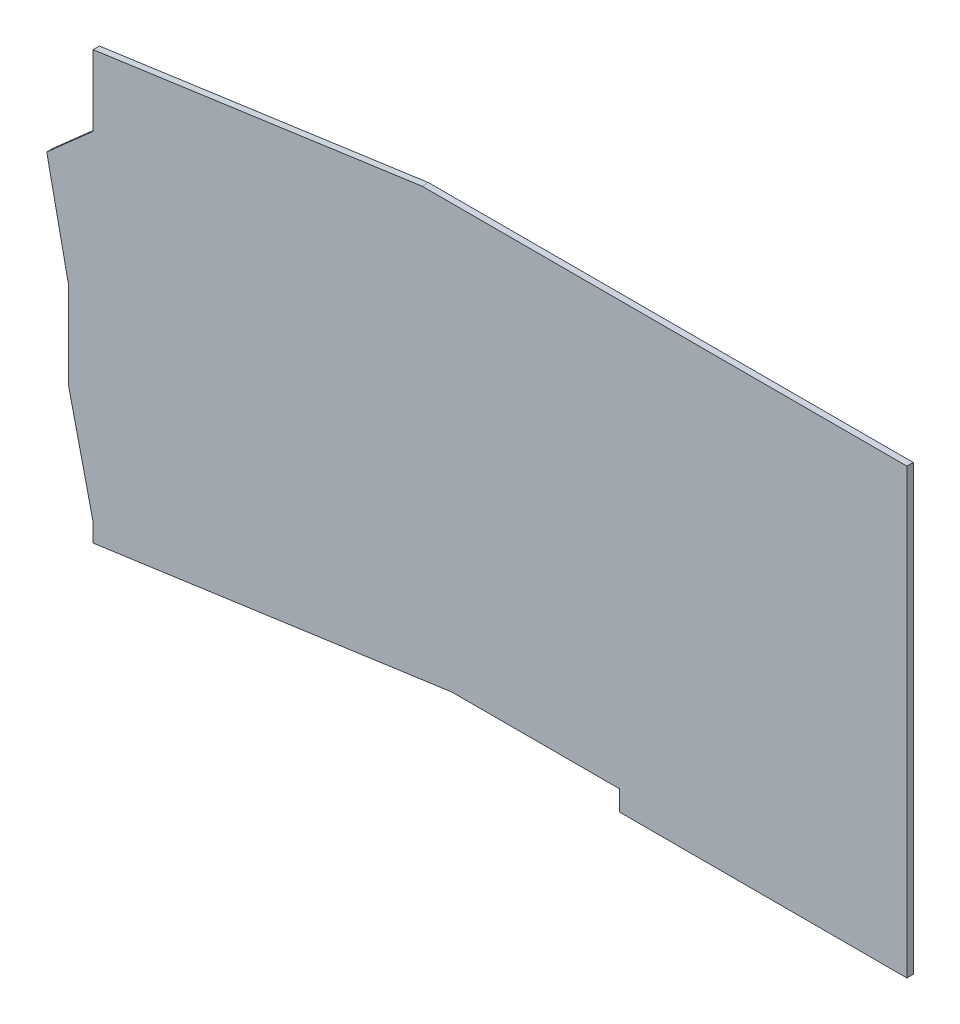
SolidWorks part; units mm, degrees
ref_plane "Front Plane" through (0, 0, 0) normal (0, 0, 1) x (1, 0, 0)
ref_plane "Top Plane" through (0, 0, 0) normal (0, 1, 0) x (1, 0, 0)
ref_plane "Right Plane" through (0, 0, 0) normal (1, 0, 0) x (0, 0, -1)
sketch "Sketch1" plane through (0, 0, 0) normal (0, 0, 1) x (1, 0, 0)
  line L13 (134.0626, 32.9236) -> (134.0626, 12.3008)
  line L14 (128.8634, 57.7786) -> (134.0626, 32.9236)
  line L15 (139.8395, 67.5001) -> (128.8634, 57.7786)
  line L16 (139.8395, 84.2477) -> (139.8395, 67.5001)
  line L17 (217.7243, 95.1942) -> (139.8395, 84.2477)
  line L18 (332.5229, 95.1942) -> (217.7243, 95.1942)
  line L19 (332.5229, -9.7622) -> (332.5229, 95.1942)
  line L20 (264.4835, -9.7622) -> (332.5229, -9.7622)
  line L21 (264.4835, -5) -> (264.4835, -9.7622)
  line L22 (224.7742, -5) -> (264.4835, -5)
  line L23 (139.8395, -16.9282) -> (224.7742, -5)
  line L24 (139.8395, -12.5918) -> (139.8395, -16.9282)
  line L25 (134.0626, 12.3008) -> (139.8395, -12.5918)
  line L26 (134.0626, 32.9236) -> (134.0626, 12.3008)
  line L27 (128.8634, 57.7786) -> (134.0626, 32.9236)
  line L28 (139.8395, 67.5001) -> (128.8634, 57.7786)
  line L29 (139.8395, 84.2477) -> (139.8395, 67.5001)
  line L30 (217.7243, 95.1942) -> (139.8395, 84.2477)
  line L31 (332.5229, 95.1942) -> (217.7243, 95.1942)
  line L32 (332.5229, -9.7622) -> (332.5229, 95.1942)
  line L33 (264.4835, -9.7622) -> (332.5229, -9.7622)
  line L34 (264.4835, -5) -> (264.4835, -9.7622)
  line L35 (224.7742, -5) -> (264.4835, -5)
  line L36 (139.8395, -16.9282) -> (224.7742, -5)
  line L37 (139.8395, -12.5918) -> (139.8395, -16.9282)
  line L38 (134.0626, 12.3008) -> (139.8395, -12.5918)
  dimension "D1" = 0
extrude "Boss-Extrude1" add sketch "Sketch1" along normal blind 1.5
